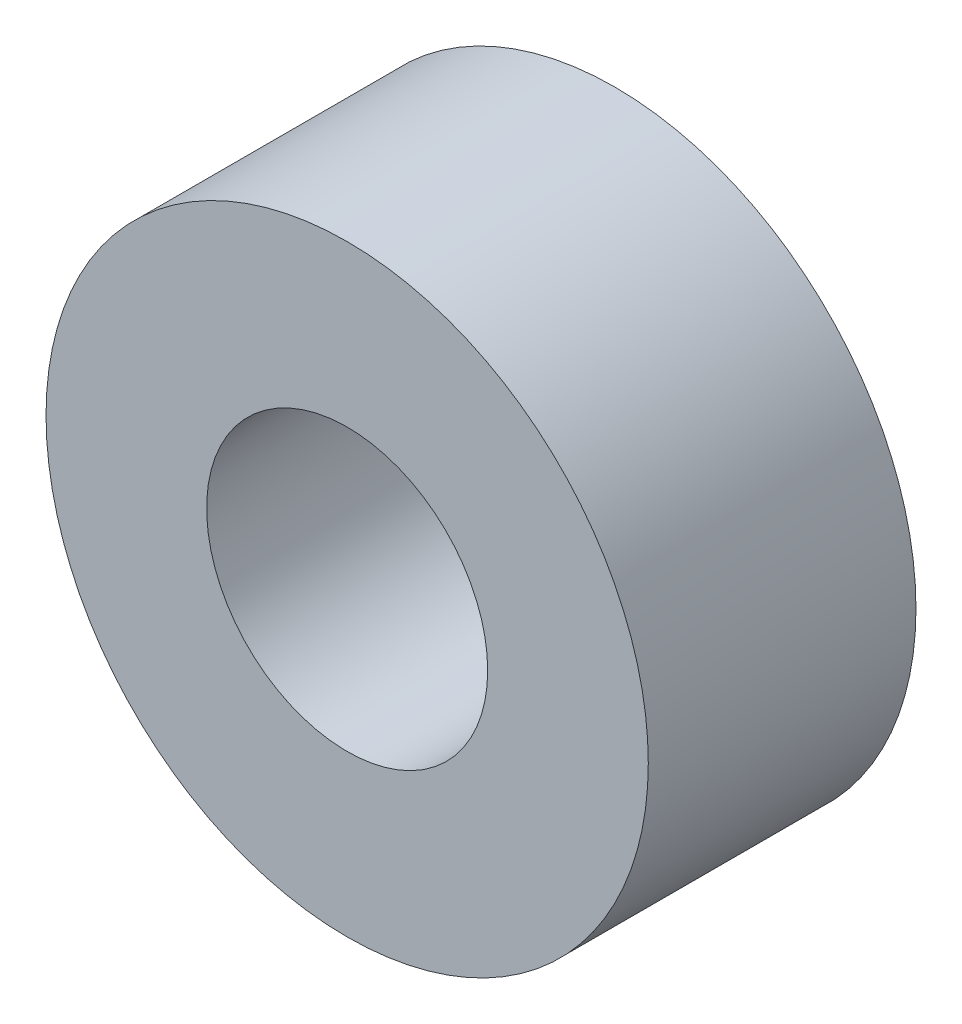
SolidWorks part; units mm, degrees
ref_plane "Front Plane" through (0, 0, 0) normal (0, 0, 1) x (1, 0, 0)
ref_plane "Top Plane" through (0, 0, 0) normal (0, 1, 0) x (1, 0, 0)
ref_plane "Right Plane" through (0, 0, 0) normal (1, 0, 0) x (0, 0, -1)
sketch "Sketch1" plane through (0, 0, 0) normal (0, 0, 1) x (1, 0, 0)
  circle A0 centre (0, 0) radius 4.5
  circle A1 centre (0, 0) radius 2.1
  dimension "D1" = 9
  dimension "D2" = 4.2
extrude "Boss-Extrude1" add sketch "Sketch1" along normal blind 4
